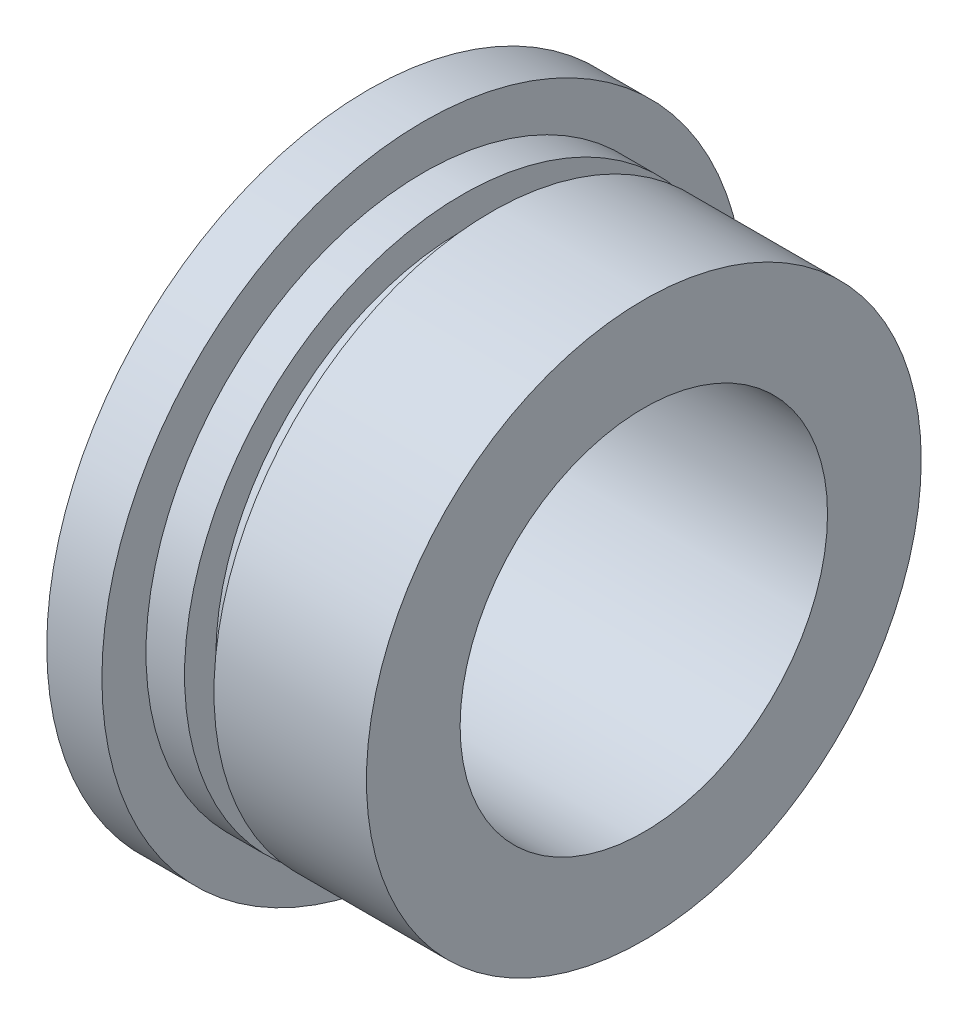
SolidWorks part; units mm, degrees
material "Phosphor bronze 10% D, UNS C52400"
ref_plane "Front Plane" through (0, 0, 0) normal (0, 0, 1) x (1, 0, 0)
ref_plane "Top Plane" through (0, 0, 0) normal (0, 1, 0) x (1, 0, 0)
ref_plane "Right Plane" through (0, 0, 0) normal (1, 0, 0) x (0, 0, -1)
sketch "Sketch1" plane through (0, 0, 0) normal (0, 0, 1) x (1, 0, 0)
  line L0 (-37.9794, 37.0852) -> (-40.9794, 37.0852)
  line L1 (-40.9794, 37.0852) -> (-40.9794, 44.5852)
  line L2 (-25.9794, 39.4852) -> (-25.9794, 44.5852)
  line L3 (-37.9794, 37.0852) -> (-37.9794, 39.4852)
  line L4 (-23.6449, 54.5852) -> (-42.8922, 54.5852) construction
  line L5 (-25.9794, 39.4852) -> (-34.2794, 39.4852)
  line L6 (-25.9794, 44.5852) -> (-40.9794, 44.5852)
  line L7 (-34.2794, 41.1852) -> (-35.8794, 41.1852)
  line L8 (-35.8794, 41.1852) -> (-35.8794, 39.4852)
  line L9 (-34.2794, 41.1852) -> (-34.2794, 39.4852)
  line L10 (-35.8794, 39.4852) -> (-37.9794, 39.4852)
revolve "Revolve1" add sketch "Sketch1" angle 360 about L4
